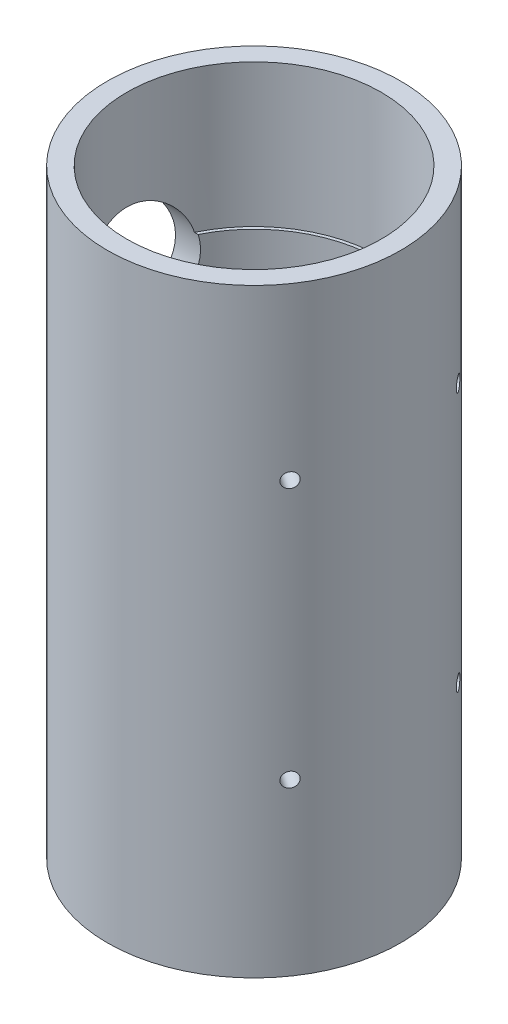
SolidWorks part; units mm, degrees
ref_plane "Front Plane" through (0, 0, 0) normal (0, 0, 1) x (1, 0, 0)
ref_plane "Top Plane" through (0, 0, 0) normal (0, 1, 0) x (1, 0, 0)
ref_plane "Right Plane" through (0, 0, 0) normal (1, 0, 0) x (0, 0, -1)
sketch "Sketch1" plane through (0, 0, 0) normal (0, 1, 0) x (1, 0, 0)
  line L0 (0, 38.25) -> (0, 45.25) construction
  circle A0 centre (0, 0) radius 38.25
  circle A1 centre (0, 0) radius 45.25
  dimension "D1" = 76.5
  dimension "D2" = 7
extrude "Boss-Extrude1" add sketch "Sketch1" along normal mid plane 185
sketch "Sketch2" plane through (0, -92.5, 0) normal (0, -1, 0) x (1, 0, 0)
  line L0 (0, 36.25) -> (0, 38.25) construction
  circle A0 centre (0, 0) radius 36.25
  circle A1 centre (0, 0) radius 38.25 construction
  circle A2 centre (0, 0) radius 38.25
  dimension "D1" = 2
extrude "Boss-Extrude2" add sketch "Sketch2" against normal blind 100 from offset 6.35 offset against normal yes
sketch "Sketch6" plane through (0, 92.5, 0) normal (0, 1, 0) x (1, 0, 0)
  line L0 (0, 38.25) -> (0, 39.25) construction
  circle A0 centre (0, 0) radius 39.25
  circle A1 centre (0, 0) radius 38.25 construction
  circle A2 centre (0, 0) radius 38.25
  dimension "D1" = 1
extrude "Cut-Extrude3" cut sketch "Sketch6" against normal blind 44
sketch "Sketch7" plane through (0, 0, 0) normal (1, 0, 0) x (0, 0, -1)
  line L0 (45.25, 92.5) -> (-45.25, 92.5) construction
  circle A0 centre (0, 44.35) radius 17.5
  dimension "D2" = 35
  dimension "D1" = 48.15
extrude "Cut-Extrude4" cut sketch "Sketch7" against normal through all
sketch "Sketch8" plane through (0, 0, 0) normal (0, 1, 0) x (1, 0, 0)
  line L0 (0, 0) -> (45.25, 0) construction
  line L1 (0, 0) -> (37.0666, 25.9543) construction
  circle A0 centre (0, 0) radius 45.25 construction
  point P5 (0, 0)
  dimension "D1" = 35
ref_plane "Plane1" through (0, 0, 0) normal (0.8192, 0, -0.5736) x (-0.5736, 0, -0.8192)
sketch "Sketch10" plane through (0, 0, 0) normal (0.8192, 0, -0.5736) x (-0.5736, 0, -0.8192)
  circle A0 centre (0, 40) radius 2.25 construction
  circle A1 centre (0, 40) radius 2.25
  circle A2 centre (0, -40) radius 2.25 construction
  circle A3 centre (0, -40) radius 2.25
extrude "Cut-Extrude5" cut sketch "Sketch10" along normal through all
mirror "Mirror1" about plane through (0, 0, 0) normal (0, 0, 1) of "Cut-Extrude5"
